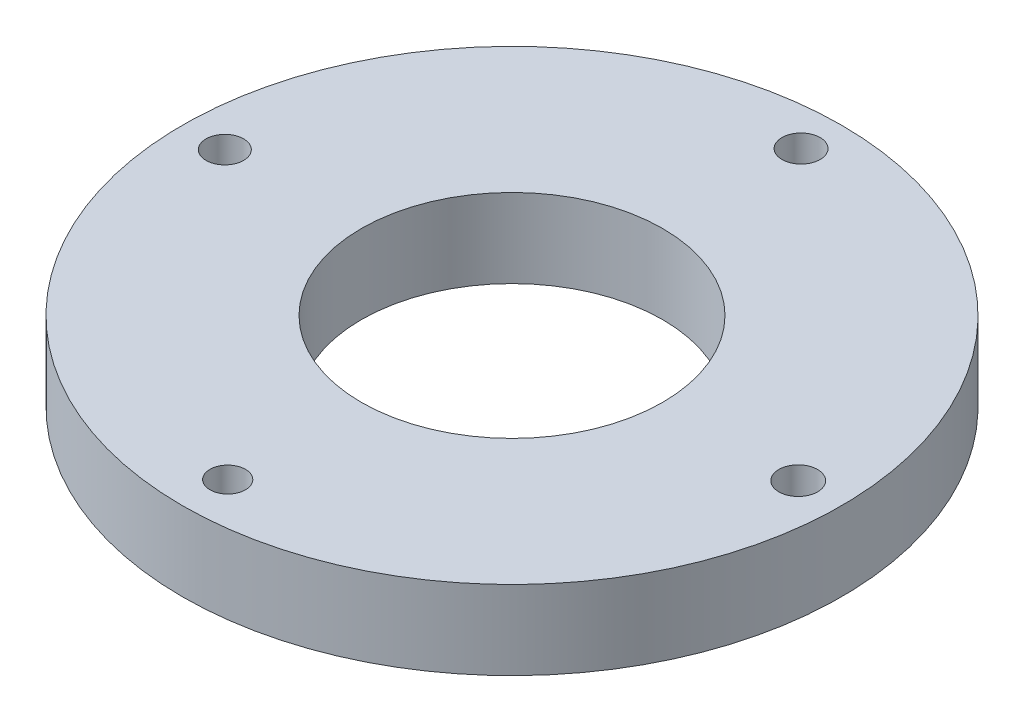
SolidWorks part; units mm, degrees
material "ABS"
ref_plane "Front Plane" through (0, 0, 0) normal (0, 0, 1) x (1, 0, 0)
ref_plane "Top Plane" through (0, 0, 0) normal (0, 1, 0) x (1, 0, 0)
ref_plane "Right Plane" through (0, 0, 0) normal (1, 0, 0) x (0, 0, -1)
sketch "Sketch1" plane through (0, 0, 0) normal (0, 1, 0) x (1, 0, 0)
  circle A0 centre (0, 0) radius 25.05
  dimension "D1" = 50.1
extrude "Boss-Extrude1" add sketch "Sketch1" along normal blind 6 contours A0
sketch "Sketch5" plane through (0, 6, 0) normal (0, 1, 0) x (1, 0, 0)
  circle A0 centre (21.755, 0) radius 1.475
  circle A1 centre (0, 21.9733) radius 1.45
  circle A2 centre (-21.8277, 0) radius 1.425
  circle A3 centre (0, -21.6095) radius 1.35
  circle A4 centre (0, 0) radius 11.45
  dimension "D1" = 2.95
  dimension "D2" = 2.9
  dimension "D3" = 2.85
  dimension "D4" = 2.7
  dimension "D5" = 22.9
extrude "Cut-Extrude2" cut sketch "Sketch5" against normal through all
